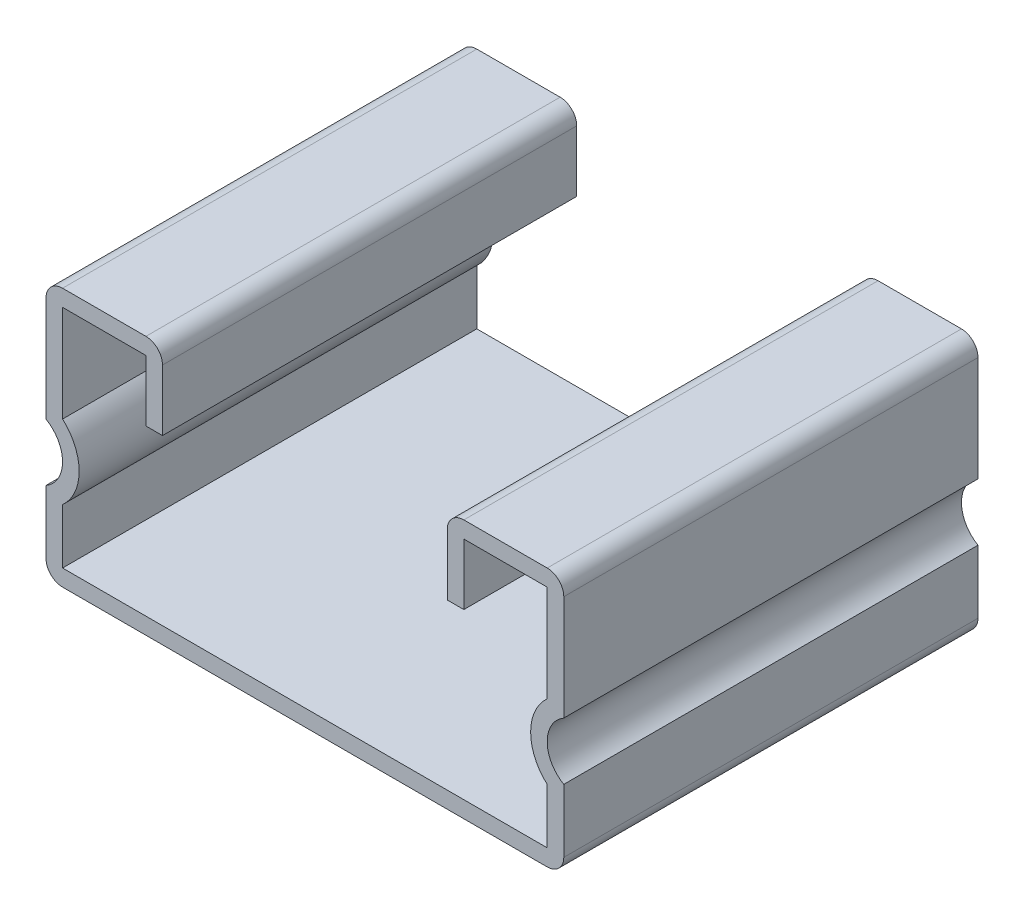
SolidWorks part; units mm, degrees
ref_plane "Plane1" through (0, 0, 0) normal (0, 0, 1) x (1, 0, 0)
ref_plane "Plane2" through (0, 0, 0) normal (0, 1, 0) x (1, 0, 0)
ref_plane "Plane3" through (0, 0, 0) normal (1, 0, 0) x (0, 0, -1)
sketch "Sketch1" plane through (0, 0, 0) normal (0, 0, 1) x (1, 0, 0)
  line L0 (-15.875, 8.2042) -> (-15.875, 1.7598)
  line L1 (-15.875, -1.7598) -> (-15.875, -5.6388)
  line L2 (-14.859, -6.6548) -> (14.859, -6.6548)
  line L3 (15.875, -5.6388) -> (15.875, -1.7598)
  line L4 (15.875, 1.7598) -> (15.875, 8.2042)
  line L5 (14.859, 9.2202) -> (9.7472, 9.2202)
  line L6 (8.7312, 8.2042) -> (8.7312, 4.4577)
  line L7 (-14.859, 9.2202) -> (-9.7472, 9.2202)
  line L8 (-8.7312, 8.2042) -> (-8.7312, 4.4577)
  line L9 (14.859, -3.9553) -> (14.859, 8.0137) construction
  line L10 (-14.859, 8.0137) -> (-14.859, -3.9553) construction
  line L11 (-9.7472, 8.2042) -> (-9.7472, 4.4577)
  line L12 (-14.859, 8.2042) -> (-9.7472, 8.2042)
  line L13 (-14.859, 8.2042) -> (-14.859, 2.2718)
  line L14 (-14.859, -2.2718) -> (-14.859, -5.6388)
  line L15 (-14.859, -5.6388) -> (14.859, -5.6388)
  line L16 (14.859, -5.6388) -> (14.859, -2.2718)
  line L17 (14.859, 2.2718) -> (14.859, 8.2042)
  line L18 (14.859, 8.2042) -> (9.7472, 8.2042)
  line L19 (9.7472, 8.2042) -> (9.7472, 4.4577)
  line L20 (-9.7472, 4.4577) -> (-8.7312, 4.4577)
  line L21 (8.7312, 4.4577) -> (9.7472, 4.4577)
  arc A0 (15.875, 1.7598) -> (15.875, -1.7598) centre (16.891, 0) ccw
  arc A1 (-15.875, -1.7598) -> (-15.875, 1.7598) centre (-16.891, 0) ccw
  arc A2 (-9.7472, 9.2202) -> (-8.7312, 8.2042) centre (-9.7472, 8.2042) cw
  arc A3 (-15.875, 8.2042) -> (-14.859, 9.2202) centre (-14.859, 8.2042) cw
  arc A4 (-14.859, -6.6548) -> (-15.875, -5.6388) centre (-14.859, -5.6388) cw
  arc A5 (15.875, -5.6388) -> (14.859, -6.6548) centre (14.859, -5.6388) cw
  arc A6 (14.859, 9.2202) -> (15.875, 8.2042) centre (14.859, 8.2042) cw
  arc A7 (8.7312, 8.2042) -> (9.7472, 9.2202) centre (9.7472, 8.2042) cw
  arc A8 (-14.859, -2.2718) -> (-14.859, 2.2718) centre (-16.891, 0) ccw
  arc A9 (14.859, 2.2718) -> (14.859, -2.2718) centre (16.891, 0) ccw
  dimension "D9" = 2.032
  dimension "D10" = 2.032
  dimension "D1" = 15.875
  dimension "Width" = 31.75
  dimension "base" = 6.6548
  dimension "ToeHt" = 9.2202
  dimension "D6" = 17.4625
  dimension "edge" = 7.1437
  dimension "Lip" = 4.7625
  dimension "gauge" = 1.016
extrude "Base-Extrude" add sketch "Sketch1" along normal mid plane 25.4
equation "\"D1@Sketch1\" = \"Width@Sketch1\" / 2"
equation "\"D6@Sketch1\" = \"Width@Sketch1\" - 2 * \"edge@Sketch1\""
equation "\"D10@Sketch1\" = 2 * \"gauge@Sketch1\""
equation "\"D9@Sketch1\" = \"D10@Sketch1\""
